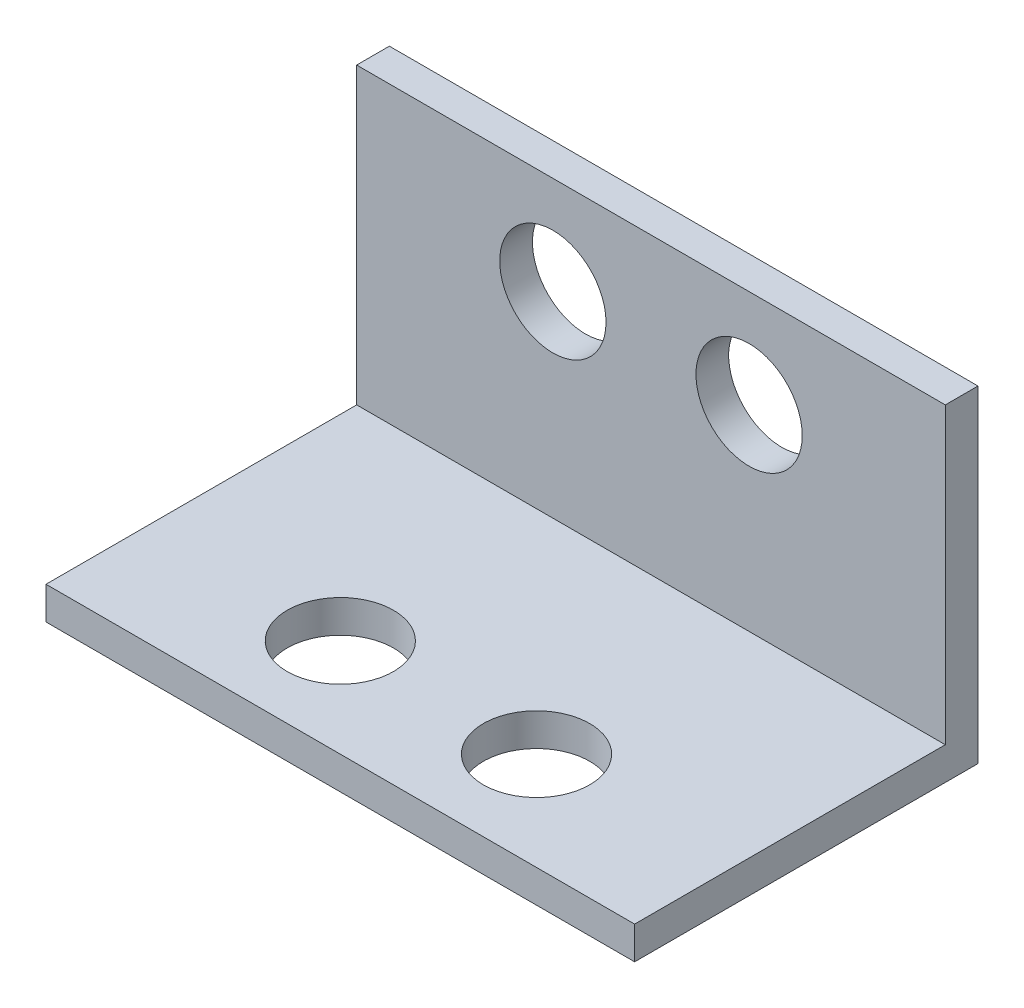
SolidWorks part; units mm, degrees
other "Markup1"
sketch "Sketch3" plane through (0, 3, -10.5) normal (0, 1, 0) x (1, 0, 0)
ref_plane "Front Plane" through (0, 0, 0) normal (0, 0, 1) x (1, 0, 0)
ref_plane "Top Plane" through (0, 0, 0) normal (0, 1, 0) x (1, 0, 0)
ref_plane "Right Plane" through (0, 0, 0) normal (1, 0, 0) x (0, 0, -1)
sketch "Sketch1" plane through (0, 0, 0) normal (0, 1, 0) x (1, 0, 0)
  line L1 (0, 0) -> (18, 0)
  line L2 (0, 0) -> (0, 10.5)
  line L3 (0, 10.5) -> (18, 10.5)
  line L4 (18, 0) -> (18, 10.5)
  circle A0 centre (6, 3) radius 1.625
  circle A1 centre (12, 3) radius 1.625
  dimension "D2" = 3.25
  dimension "D3" = 6
  dimension "D4" = 3
  dimension "D5" = 3
  dimension "D6" = 6
  dimension "D7" = 3.25
  dimension "D1" = 10.5
  dimension "18" = 18
extrude "Boss-Extrude1" add sketch "Sketch1" along normal blind 1
sketch "Sketch2" plane through (0, 1, 0) normal (0, 1, 0) x (1, 0, 0)
  line L0 (18, 0) -> (18, 10.5) construction
  line L1 (0, 10.5) -> (18, 10.5)
  line L2 (0, 10.5) -> (0, 9.5)
  line L3 (0, 9.5) -> (18, 9.5)
  line L4 (18, 10.5) -> (18, 9.5)
  dimension "D1" = 1
extrude "Boss-Extrude2" add sketch "Sketch2" along normal blind 9
sketch "Sketch4" plane through (0, 0, -9.5) normal (0, 0, 1) x (1, 0, 0)
  line L0 (0, 10) -> (0, 1) construction
  line L1 (0, 10) -> (18, 10) construction
  circle A0 centre (6, 7) radius 1.625
  circle A1 centre (12, 7) radius 1.625
  dimension "D1" = 3.25
  dimension "D2" = 3.25
  dimension "D3" = 6
  dimension "D4" = 6
  dimension "D5" = 3
  dimension "D6" = 3
extrude "Cut-Extrude1" cut sketch "Sketch4" against normal through all
